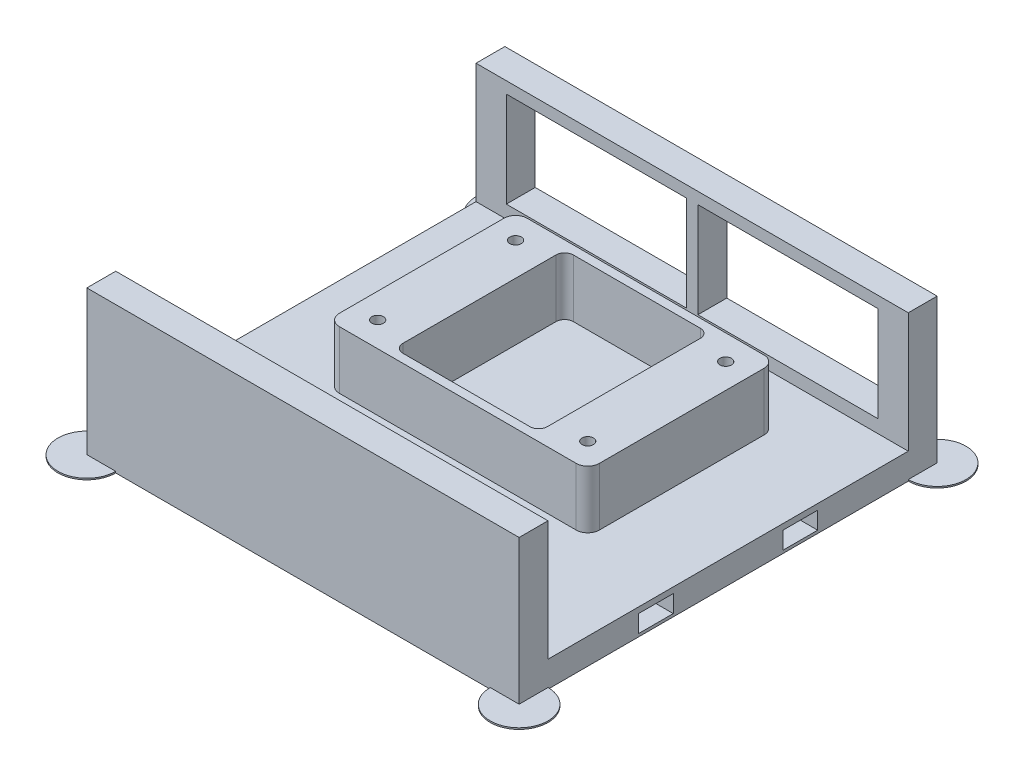
SolidWorks part; units mm, degrees
material "ABS"
ref_plane "Front Plane" through (0, 0, 0) normal (0, 0, 1) x (1, 0, 0)
ref_plane "Top Plane" through (0, 0, 0) normal (0, 1, 0) x (1, 0, 0)
ref_plane "Right Plane" through (0, 0, 0) normal (1, 0, 0) x (0, 0, -1)
sketch "Sketch1" plane through (0, 0, 0) normal (0, 1, 0) x (1, 0, 0)
  line L0 (-150, 0) -> (150, 0) construction
  line L1 (-150, 45) -> (-150, -45)
  line L2 (140.0883, -41.1583) -> (79.948, -63.0476) construction
  line L3 (-140.0883, 41.1583) -> (-142.4825, 47.7362) construction
  line L4 (-140.0883, 41.1583) -> (-79.948, 63.0476) construction
  line L5 (-150, 45) -> (-74.8246, 72.3616)
  line L6 (-79.948, 63.0476) -> (-82.3421, 69.6255) construction
  line L7 (-143, 32) -> (-143, -32) construction
  line L8 (-140.0883, -41.1583) -> (-142.4825, -47.7362) construction
  line L9 (-79.948, -63.0476) -> (-82.3421, -69.6255) construction
  line L10 (-140.0883, -41.1583) -> (-79.948, -63.0476) construction
  line L11 (-150, -45) -> (-74.8246, -72.3616)
  line L12 (0, 74.8501) -> (0, -82.9126) construction
  line L13 (79.948, -63.0476) -> (82.3421, -69.6255) construction
  line L14 (140.0883, -41.1583) -> (142.4825, -47.7362) construction
  line L15 (143, 32) -> (143, -32) construction
  line L16 (79.948, 63.0476) -> (82.3421, 69.6255) construction
  line L17 (140.0883, 41.1583) -> (79.948, 63.0476) construction
  line L18 (140.0883, 41.1583) -> (142.4825, 47.7362) construction
  line L19 (150, -45) -> (74.8246, -72.3616)
  line L20 (150, 45) -> (74.8246, 72.3616)
  line L21 (150, 45) -> (150, -45)
  line L22 (-74.8246, 72.3616) -> (74.8246, 72.3616)
  line L23 (-74.8246, -72.3616) -> (74.8246, -72.3616)
  point P0 (0, 0)
  point P3 (-150, 0)
  point P10 (-143, 0)
  point P13 (0, 0)
  point P37 (143, 0)
  dimension "D1" = 7
  dimension "D2" = 90
  dimension "D3" = 64
  dimension "D4" = 300
  dimension "D5" = 7
  dimension "D6" = 8
  dimension "D7" = 80
  dimension "D8" = 110
extrude "Boss-Extrude1" add sketch "Sketch1" along normal blind 8
sketch "Sketch2" plane through (0, 8, 0) normal (0, 1, 0) x (1, 0, 0)
  line L0 (0, 72.3616) -> (0, -72.3616) construction
  line L1 (74.8246, 72.3616) -> (-74.8246, 72.3616) construction
  line L2 (-74.8246, -72.3616) -> (74.8246, -72.3616) construction
  line L3 (-74.8246, -72.3616) -> (-74.8246, -62.3616) construction
  line L4 (-74.8246, -62.3616) -> (-64.3246, -62.3616) construction
  line L5 (-64.3246, -62.3616) -> (-64.3246, -72.3616) construction
  line L6 (-64.3246, -72.3616) -> (-74.8246, -72.3616) construction
  line L7 (64.3246, -72.3616) -> (74.8246, -72.3616) construction
  line L8 (64.3246, -62.3616) -> (64.3246, -72.3616) construction
  line L9 (74.8246, -62.3616) -> (64.3246, -62.3616) construction
  line L10 (74.8246, -72.3616) -> (74.8246, -62.3616) construction
  line L11 (-150, 0) -> (150, 0) construction
  line L12 (-150, 45) -> (-150, -45) construction
  line L13 (150, -45) -> (150, 45) construction
  line L14 (74.8246, 72.3616) -> (74.8246, 62.3616)
  line L15 (74.8246, 62.3616) -> (64.3246, 62.3616)
  line L16 (64.3246, 62.3616) -> (64.3246, 72.3616)
  line L17 (64.3246, 72.3616) -> (74.8246, 72.3616)
  line L18 (-64.3246, 72.3616) -> (-74.8246, 72.3616)
  line L19 (-64.3246, 62.3616) -> (-64.3246, 72.3616)
  line L20 (-74.8246, 62.3616) -> (-64.3246, 62.3616)
  line L21 (-74.8246, 72.3616) -> (-74.8246, 62.3616)
  dimension "D1" = 10.5
  dimension "D2" = 10
extrude "Boss-Extrude2" add sketch "Sketch2" along normal blind 37.5
sketch "Sketch4" plane through (0, 8, 0) normal (0, 1, 0) x (1, 0, 0)
  line L1 (-64.3246, 72.3616) -> (64.3246, 72.3616)
  line L2 (-64.3246, 72.3616) -> (-64.3246, 62.3616)
  line L3 (-64.3246, 62.3616) -> (64.3246, 62.3616)
  line L4 (64.3246, 72.3616) -> (64.3246, 62.3616)
extrude "Boss-Extrude4" add sketch "Sketch4" along normal blind 4.5
sketch "Sketch5" plane through (0, 8, 0) normal (0, 1, 0) x (1, 0, 0)
  line L0 (-74.8246, 62.3616) -> (-87.0406, 57.9153)
  line L1 (-74.8246, 72.3616) -> (-150, 45) construction
  line L2 (-74.8246, 72.3616) -> (-74.8246, 62.3616)
  line L3 (-74.8246, 72.3616) -> (-150, 45)
  line L4 (-87.0406, 57.9153) -> (-140.6031, 38.4202)
  line L5 (-150, 45) -> (-140.6031, 38.4202) construction
  line L6 (-74.8246, -72.3616) -> (-74.8246, -62.3616)
  line L7 (-140.6031, 38.4202) -> (-143.4222, 37.3941)
  line L8 (-150, 45) -> (-143.4222, 37.3941) construction
  line L9 (-150, 0) -> (-74.8246, 0) construction
  line L10 (-150, 45) -> (-150, -45) construction
  line L11 (-79.6003, 0) -> (86.9407, 0) construction
  line L12 (-124.0599, 0) -> (-121.8599, 0) construction
  line L13 (-74.8246, -62.3616) -> (-87.0406, -57.9153)
  line L14 (-140.6031, -38.4202) -> (-143.4222, -37.3941)
  line L15 (-87.0406, -57.9153) -> (-140.6031, -38.4202)
  line L16 (-150, -45) -> (-143.4222, -37.3941) construction
  line L17 (-74.8246, -72.3616) -> (-150, -45)
  line L18 (-143.4222, 37.3941) -> (-143.4222, -37.3941)
  line L19 (-150, 45) -> (-150, -45)
  line L20 (0, 72.1209) -> (0, -72.3616) construction
  line L21 (-74.8246, -72.3616) -> (74.8246, -72.3616) construction
  line L22 (150, -45) -> (143.4222, -37.3941) construction
  line L23 (150, 0) -> (74.8246, 0) construction
  line L24 (150, 45) -> (143.4222, 37.3941) construction
  line L25 (150, 45) -> (140.6031, 38.4202) construction
  line L26 (150, 45) -> (150, -45)
  line L27 (143.4222, 37.3941) -> (143.4222, -37.3941)
  line L28 (74.8246, -72.3616) -> (150, -45)
  line L29 (87.0406, -57.9153) -> (140.6031, -38.4202)
  line L30 (140.6031, -38.4202) -> (143.4222, -37.3941)
  line L31 (74.8246, -62.3616) -> (87.0406, -57.9153)
  line L32 (140.6031, 38.4202) -> (143.4222, 37.3941)
  line L33 (74.8246, -72.3616) -> (74.8246, -62.3616)
  line L34 (87.0406, 57.9153) -> (140.6031, 38.4202)
  line L35 (74.8246, 72.3616) -> (150, 45)
  line L36 (74.8246, 72.3616) -> (74.8246, 62.3616)
  line L37 (74.8246, 62.3616) -> (87.0406, 57.9153)
  dimension "D1" = 13
  dimension "D2" = 55
  dimension "D3" = 3
extrude "Boss-Extrude5" add sketch "Sketch5" along normal blind 10
sketch "Sketch6" plane through (0, 45.5, 0) normal (0, 1, 0) x (1, 0, 0)
  line L1 (74.8246, 72.3616) -> (-74.8246, 72.3616)
  line L2 (74.8246, 72.3616) -> (74.8246, 62.3616)
  line L3 (74.8246, 62.3616) -> (-74.8246, 62.3616)
  line L4 (-74.8246, 72.3616) -> (-74.8246, 62.3616)
extrude "Boss-Extrude6" add sketch "Sketch6" along normal blind 4
sketch "Sketch7" plane through (32.0094, 0, -87.9451) normal (0.342, 0, -0.9397) x (-0.9397, 0, -0.342)
  line L0 (-85.563, 18) -> (-85.563, 0) construction
  line L1 (-125.563, 18) -> (-45.563, 18) construction
  line L2 (-125.563, 0) -> (-45.563, 0) construction
  line L3 (-113.853, 13) -> (-85.563, 13) construction
  circle A0 centre (-113.853, 13) radius 2.5
  circle A1 centre (-57.273, 13) radius 2.5
  dimension "D1" = 56.58
  dimension "D2" = 5
  dimension "D3" = 5
extrude "Cut-Extrude1" cut sketch "Sketch7" against normal up to next
ref_plane "Plane1" through (0, 0, 0) normal (1, 0, 0) x (0, 0, -1)
mirror "Mirror1" about plane through (0, 0, 0) normal (1, 0, 0) of "Cut-Extrude1"
ref_plane "Plane2" through (0, 0, 0) normal (0, 0, -1) x (-1, 0, 0)
mirror "Mirror2" about plane through (0, 0, 0) normal (0, 0, -1) of "Cut-Extrude1", "Mirror1"
sketch "Sketch8" plane through (150, 0, 0) normal (1, 0, 0) x (0, 0, -1)
  line L0 (0, 18) -> (0, 0) construction
  line L1 (-45, 18) -> (45, 18) construction
  line L2 (-28.29, 13) -> (28.29, 13) construction
  line L3 (0, -27.775) -> (0, 27.775) construction
  circle A0 centre (-28.29, 13) radius 2.5
  circle A1 centre (28.29, 13) radius 2.5
  point P8 (0, 13)
  dimension "D1" = 56.58
  dimension "D3" = 5
  dimension "D2" = 5
extrude "Cut-Extrude2" cut sketch "Sketch8" against normal up to next
mirror "Mirror3" about plane through (0, 0, 0) normal (1, 0, 0) of "Cut-Extrude2"
sketch "Sketch9" plane through (0, 18, 0) normal (0, 1, 0) x (1, 0, 0)
  line L0 (143.4222, 23) -> (150, 23)
  line L1 (143.4222, 37.3941) -> (143.4222, -37.3941) construction
  line L2 (150, -45) -> (150, 45) construction
  line L3 (150, 23) -> (150, 45)
  line L4 (150, 45) -> (134.0252, 50.8143)
  line L5 (150, 45) -> (74.8246, 72.3616) construction
  line L6 (134.0252, 50.8143) -> (130.8113, 41.9841)
  line L7 (74.8246, 62.3616) -> (143.4222, 37.3941) construction
  line L8 (130.8113, 41.9841) -> (143.4222, 37.3941)
  line L9 (143.4222, 37.3941) -> (143.4222, 23)
  line L12 (74.8246, 72.3616) -> (90.7994, 66.5473)
  line L13 (90.7994, 66.5473) -> (87.5854, 57.717)
  line L14 (87.5854, 57.717) -> (74.8246, 62.3616)
  line L15 (74.8246, 72.3616) -> (74.8246, 62.3616) construction
  line L16 (74.8246, 62.3616) -> (74.8246, 72.3616)
  line L17 (0, -70.7131) -> (0, 92.4677) construction
  line L18 (-74.8246, 62.3616) -> (-74.8246, 72.3616)
  line L19 (-87.5854, 57.717) -> (-74.8246, 62.3616)
  line L20 (-90.7994, 66.5473) -> (-87.5854, 57.717)
  line L21 (-74.8246, 72.3616) -> (-90.7994, 66.5473)
  line L22 (-143.4222, 37.3941) -> (-143.4222, 23)
  line L23 (-130.8113, 41.9841) -> (-143.4222, 37.3941)
  line L24 (-134.0252, 50.8143) -> (-130.8113, 41.9841)
  line L25 (-150, 45) -> (-134.0252, 50.8143)
  line L26 (-150, 23) -> (-150, 45)
  line L27 (-143.4222, 23) -> (-150, 23)
  line L28 (150, 0) -> (-150, 0) construction
  line L29 (-150, 45) -> (-150, -45) construction
  line L30 (143.4222, -37.3941) -> (143.4222, -23)
  line L31 (130.8113, -41.9841) -> (143.4222, -37.3941)
  line L32 (134.0252, -50.8143) -> (130.8113, -41.9841)
  line L33 (150, -45) -> (134.0252, -50.8143)
  line L34 (150, -23) -> (150, -45)
  line L35 (143.4222, -23) -> (150, -23)
  line L36 (-143.4222, -23) -> (-150, -23)
  line L37 (-150, -23) -> (-150, -45)
  line L38 (-150, -45) -> (-134.0252, -50.8143)
  line L39 (-134.0252, -50.8143) -> (-130.8113, -41.9841)
  line L40 (-130.8113, -41.9841) -> (-143.4222, -37.3941)
  line L41 (-143.4222, -37.3941) -> (-143.4222, -23)
  line L42 (-74.8246, -72.3616) -> (-90.7994, -66.5473)
  line L43 (-90.7994, -66.5473) -> (-87.5854, -57.717)
  line L44 (-87.5854, -57.717) -> (-74.8246, -62.3616)
  line L45 (-74.8246, -62.3616) -> (-74.8246, -72.3616)
  line L46 (74.8246, -62.3616) -> (74.8246, -72.3616)
  line L47 (87.5854, -57.717) -> (74.8246, -62.3616)
  line L48 (90.7994, -66.5473) -> (87.5854, -57.717)
  line L49 (74.8246, -72.3616) -> (90.7994, -66.5473)
  dimension "D1" = 22
  dimension "D2" = 17
  dimension "D3" = 17
extrude "Boss-Extrude8" add sketch "Sketch9" along normal blind 63
sketch "Sketch10" plane through (32.0094, 0, -87.9451) normal (0.342, 0, -0.9397) x (-0.9397, 0, -0.342)
  line L0 (-85.563, 0) -> (-85.563, 86.9159) construction
  line L1 (-125.563, 0) -> (-45.563, 0) construction
  line L2 (-113.853, 13) -> (-113.853, 74) construction
  circle A0 centre (-113.853, 74) radius 2.5
  circle A1 centre (-113.853, 13) radius 2.5 construction
  circle A2 centre (-57.273, 74) radius 2.5
  dimension "D1" = 61
extrude "Cut-Extrude3" cut sketch "Sketch10" against normal up to next
mirror "Mirror4" about plane through (0, 0, 0) normal (1, 0, 0) of "Cut-Extrude3"
mirror "Mirror5" about plane through (0, 0, 0) normal (0, 0, -1) of "Cut-Extrude3", "Mirror4"
sketch "Sketch11" plane through (150, 0, 0) normal (1, 0, 0) x (0, 0, -1)
  line L0 (-28.29, 13) -> (-28.29, 74) construction
  line L1 (0, 18) -> (0, 79.1024) construction
  line L2 (-23, 18) -> (23, 18) construction
  circle A0 centre (-28.29, 74) radius 2.5
  circle A1 centre (-28.29, 13) radius 2.5 construction
  circle A2 centre (28.29, 74) radius 2.5
  dimension "D1" = 61
extrude "Cut-Extrude4" cut sketch "Sketch11" against normal up to next
mirror "Mirror6" about plane through (0, 0, 0) normal (1, 0, 0) of "Cut-Extrude4"
sketch "Sketch12" plane through (0, 81, 0) normal (0, 1, 0) x (1, 0, 0)
  line L0 (130.8113, 41.9841) -> (87.5854, 57.717)
  line L1 (87.5854, 57.717) -> (90.7994, 66.5473)
  line L2 (90.7994, 66.5473) -> (134.0252, 50.8143)
  line L3 (134.0252, 50.8143) -> (130.8113, 41.9841)
  line L4 (0, 103.9036) -> (0, -116.4859) construction
  line L5 (143.4222, 23) -> (150, 23)
  line L6 (143.4222, 23) -> (143.4222, -23)
  line L7 (143.4222, -23) -> (150, -23)
  line L8 (150, 23) -> (150, -23)
  line L9 (150, 0) -> (-150, 0) construction
  line L10 (-150, 23) -> (-150, -23) construction
  line L11 (134.0252, -50.8143) -> (130.8113, -41.9841)
  line L12 (90.7994, -66.5473) -> (134.0252, -50.8143)
  line L13 (87.5854, -57.717) -> (90.7994, -66.5473)
  line L14 (130.8113, -41.9841) -> (87.5854, -57.717)
  line L15 (-130.8113, -41.9841) -> (-87.5854, -57.717)
  line L16 (-87.5854, -57.717) -> (-90.7994, -66.5473)
  line L17 (-90.7994, -66.5473) -> (-134.0252, -50.8143)
  line L18 (-134.0252, -50.8143) -> (-130.8113, -41.9841)
  line L19 (-150, 23) -> (-150, -23)
  line L20 (-143.4222, -23) -> (-150, -23)
  line L21 (-143.4222, 23) -> (-143.4222, -23)
  line L22 (-143.4222, 23) -> (-150, 23)
  line L23 (-134.0252, 50.8143) -> (-130.8113, 41.9841)
  line L24 (-90.7994, 66.5473) -> (-134.0252, 50.8143)
  line L25 (-87.5854, 57.717) -> (-90.7994, 66.5473)
  line L26 (-130.8113, 41.9841) -> (-87.5854, 57.717)
extrude "Boss-Extrude9" add sketch "Sketch12" against normal blind 12
sketch "Sketch13" plane through (0, 8, 0) normal (0, 1, 0) x (1, 0, 0)
  line L0 (0, 62.3616) -> (0, -72.3616) construction
  line L1 (-41, 46.2316) -> (-29, 46.2316)
  line L2 (-45, 42.2316) -> (-45, -14.7684)
  line L3 (-41, -18.7684) -> (-29, -18.7684)
  line L4 (45, 42.2316) -> (45, -14.7684)
  line L5 (-74.8246, 62.3616) -> (74.8246, 62.3616) construction
  line L6 (-74.8246, -72.3616) -> (74.8246, -72.3616) construction
  line L7 (-25, 40.2316) -> (-25, -12.7684)
  line L8 (25, 40.2316) -> (25, -12.7684)
  line L9 (29, 46.2316) -> (41, 46.2316)
  line L10 (29, -18.7684) -> (41, -18.7684)
  line L11 (-25, 46.2316) -> (25, 46.2316) construction
  line L12 (-25, -18.7684) -> (25, -18.7684) construction
  line L13 (-29, 46.2316) -> (29, 46.2316)
  line L14 (-22, 43.2316) -> (22, 43.2316)
  line L15 (-22, -15.7684) -> (22, -15.7684)
  line L16 (-29, -18.7684) -> (29, -18.7684)
  arc A0 (-45, -14.7684) -> (-41, -18.7684) centre (-41, -14.7684) ccw
  arc A1 (41, -18.7684) -> (45, -14.7684) centre (41, -14.7684) ccw
  arc A2 (41, 46.2316) -> (45, 42.2316) centre (41, 42.2316) cw
  arc A3 (-41, 46.2316) -> (-45, 42.2316) centre (-41, 42.2316) ccw
  arc A4 (-25, -12.7684) -> (-22, -15.7684) centre (-22, -12.7684) ccw
  arc A5 (25, -12.7684) -> (22, -15.7684) centre (22, -12.7684) cw
  arc A6 (25, 40.2316) -> (22, 43.2316) centre (22, 40.2316) ccw
  arc A7 (-25, 40.2316) -> (-22, 43.2316) centre (-22, 40.2316) cw
  point P10 (0, 46.2316)
  point P15 (45, -18.7684)
  point P18 (45, 46.2316)
  point P21 (-45, 46.2316)
  dimension "D4" = 4
  dimension "D7" = 3
  dimension "D9" = 3
  dimension "D1" = 65
  dimension "D2" = 90
  dimension "D3" = 16.13
  dimension "D5" = 20
  dimension "D6" = 25
  dimension "D8" = 3
extrude "Boss-Extrude10" add sketch "Sketch13" along normal blind 20
sketch "Sketch14" plane through (0, 28, 0) normal (0, 1, 0) x (1, 0, 0)
  line L0 (-45, 42.2316) -> (-45, -14.7684) construction
  line L1 (-36.37, 37.6066) -> (-36.37, -10.1434) construction
  line L2 (-45, 13.7316) -> (-25, 13.7316) construction
  line L3 (-25, -12.7684) -> (-25, 40.2316) construction
  circle A0 centre (-36.37, 37.6066) radius 2
  circle A1 centre (-36.37, -10.1434) radius 2
  point P10 (-36.37, 13.7316)
  dimension "D1" = 4
  dimension "D2" = 47.75
  dimension "D3" = 8.63
extrude "Cut-Extrude5" cut sketch "Sketch14" against normal blind 10
mirror "Mirror7" about plane through (0, 0, 0) normal (1, 0, 0) of "Cut-Extrude5"
sketch "Sketch15" plane through (0, 8, 0) normal (0, 1, 0) x (1, 0, 0)
  line L1 (-74.8246, -72.3616) -> (74.8246, -72.3616)
  line L2 (-74.8246, -72.3616) -> (-74.8246, -62.3616)
  line L3 (-74.8246, -62.3616) -> (74.8246, -62.3616)
  line L4 (74.8246, -72.3616) -> (74.8246, -62.3616)
extrude "Boss-Extrude11" add sketch "Sketch15" along normal blind 41.5
sketch "Sketch16" plane through (0, 0, -72.3616) normal (0, 0, -1) x (-1, 0, 0)
  line L0 (-74.8246, 81) -> (-47.5, 81)
  line L1 (0, 0) -> (0, 104.0722) construction
  line L2 (0, 45.1) -> (0, -45.1) construction
  line L3 (74.8246, 81) -> (47.5, 81)
  line L4 (-74.8246, 49.5) -> (74.8246, 49.5) construction
  line L5 (-74.8246, 81) -> (-74.8246, 49.5)
  line L6 (-74.8246, 49.5) -> (74.8246, 49.5)
  line L7 (74.8246, 49.5) -> (74.8246, 81)
  arc A0 (-47.5, 81) -> (47.5, 81) centre (0, 101.0635) ccw
  dimension "D1" = 95
sketch "Sketch17" plane through (0, 81, 0) normal (0, 1, 0) x (1, 0, 0)
  line L0 (150, -45) -> (123.1193, -26.178) construction
  line L1 (150, 0) -> (-150, 0) construction
  line L2 (150, -45) -> (150, 45) construction
  line L3 (-150, 45) -> (-150, -45) construction
  line L4 (0, 76.5626) -> (0, -108.8084) construction
  circle A0 centre (145.0851, -41.5585) radius 2
  circle A1 centre (145.0851, 41.5585) radius 2
  circle A2 centre (-145.0851, 41.5585) radius 2
  circle A3 centre (-145.0851, -41.5585) radius 2
  dimension "D2" = 4
  dimension "D1" = 55
  dimension "D3" = 6
extrude "Cut-Extrude6" cut sketch "Sketch17" against normal blind 10
sketch "Esquisse1" plane through (0, 8, 0) normal (0, 1, 0) x (1, 0, 0)
  line L0 (-132, 21) -> (-132, -21)
  line L1 (-132, -21) -> (-120, -21)
  line L2 (-120, -21) -> (-120, 21)
  line L3 (-120, 21) -> (-132, 21)
  line L4 (0, 62.3616) -> (0, -62.3616) construction
  line L5 (-74.8246, 62.3616) -> (74.8246, 62.3616) construction
  line L6 (74.8246, -62.3616) -> (-74.8246, -62.3616) construction
  line L7 (120, 21) -> (132, 21)
  line L8 (120, -21) -> (120, 21)
  line L9 (132, -21) -> (120, -21)
  line L10 (132, 21) -> (132, -21)
  line L11 (-150, 0) -> (150, 0) construction
  line L12 (-150, 45) -> (-150, -45) construction
  line L13 (150, -45) -> (150, 45) construction
  line L14 (-74.8246, 62.3616) -> (-74.8246, -62.3616) construction
  line L15 (-95.8246, 31) -> (-53.8246, 31)
  line L16 (-95.8246, 31) -> (-95.8246, 19)
  line L17 (-95.8246, 19) -> (-53.8246, 19)
  line L18 (-53.8246, 31) -> (-53.8246, 19)
  line L19 (-95.8246, 31) -> (-53.8246, 19) construction
  line L20 (-95.8246, 19) -> (-53.8246, 31) construction
  line L21 (-95.8246, -19) -> (-53.8246, -31) construction
  line L22 (-95.8246, -31) -> (-53.8246, -19) construction
  line L23 (-53.8246, -31) -> (-53.8246, -19)
  line L24 (-95.8246, -19) -> (-53.8246, -19)
  line L25 (-95.8246, -31) -> (-95.8246, -19)
  line L26 (-95.8246, -31) -> (-53.8246, -31)
  line L27 (95.8246, -31) -> (53.8246, -19) construction
  line L28 (95.8246, -19) -> (53.8246, -31) construction
  line L29 (95.8246, 19) -> (53.8246, 31) construction
  line L30 (95.8246, 31) -> (53.8246, 19) construction
  line L31 (95.8246, -31) -> (53.8246, -31)
  line L32 (95.8246, -31) -> (95.8246, -19)
  line L33 (95.8246, -19) -> (53.8246, -19)
  line L34 (53.8246, -31) -> (53.8246, -19)
  line L35 (53.8246, 31) -> (53.8246, 19)
  line L36 (95.8246, 19) -> (53.8246, 19)
  line L37 (95.8246, 31) -> (95.8246, 19)
  line L38 (95.8246, 31) -> (53.8246, 31)
  point P20 (-120, 0)
  point P21 (-74.8246, 25)
  point P34 (-74.8246, -25)
  point P43 (74.8246, -25)
  point P44 (74.8246, 25)
  dimension "D1" = 12
  dimension "D2" = 42
  dimension "D3" = 120
  dimension "D4" = 25
extrude "Enlèv. mat.-Extru.1" cut sketch "Esquisse1" against normal blind 6 from offset 2 offset against normal yes
sketch "Esquisse2" plane through (0, 0, 0) normal (0, -1, 0) x (1, 0, 0)
  line L8 (-150, -45) -> (-74.8246, -72.3616)
  line L9 (-74.8246, -72.3616) -> (74.8246, -72.3616)
  line L10 (74.8246, -72.3616) -> (150, -45)
  line L11 (150, -45) -> (150, 45)
  line L12 (150, 45) -> (74.8246, 72.3616)
  line L13 (74.8246, 72.3616) -> (-74.8246, 72.3616)
  line L14 (-74.8246, 72.3616) -> (-150, 45)
  line L15 (-150, 45) -> (-150, -45)
  line L16 (-150, -45) -> (-74.8246, -72.3616)
  line L17 (-74.8246, -72.3616) -> (74.8246, -72.3616)
  line L18 (74.8246, -72.3616) -> (150, -45)
  line L19 (150, -45) -> (150, 45)
  line L20 (150, 45) -> (74.8246, 72.3616)
  line L21 (74.8246, 72.3616) -> (-74.8246, 72.3616)
  line L22 (-74.8246, 72.3616) -> (-150, 45)
  line L23 (-150, 45) -> (-150, -45)
  dimension "D1" = 0
extrude "Boss.-Extru.1" add sketch "Esquisse2" along normal blind 1
fillet "Congé1" radius 5 4 edges at (150, 40, 45) (150, 40, -45) (-150, 40, -45) (-150, 40, 45)
sketch "Esquisse3" plane through (-32.0094, 0, 87.9451) normal (-0.342, 0, 0.9397) x (0.9397, 0, 0.342)
  line L0 (-62.563, 69) -> (-62.563, 18) construction
  line L1 (-108.563, 69) -> (-56.563, 69)
  line L2 (-108.563, 69) -> (-108.563, 14)
  line L3 (-108.563, 14) -> (-56.563, 14)
  line L4 (-56.563, 69) -> (-56.563, 14)
  line L5 (-108.563, 18) -> (-62.563, 18) construction
  circle A0 centre (-57.273, 13) radius 2.5
  circle A2 centre (-57.273, 13) radius 2.5 construction
  line M5 (-62.563, 69) -> (-62.563, 18)
  line M6 (-62.563, 18) -> (-108.563, 18)
  circle M9 centre (-57.273, 13) radius 2.5
  dimension "D1" = 6
  dimension "D2" = 4
extrude "Enlèv. mat.-Extru.2" cut sketch "Esquisse3" against normal blind 10 contours L4 L1 L2 L3 M5 M6 M9
sketch "Esquisse5" plane through (-150, 0, 0) normal (-1, 0, 0) x (0, 0, 1)
  line L0 (23, 69) -> (23, 18) construction
  line L1 (-23, 69) -> (29, 69)
  line L2 (-23, 69) -> (-23, 14)
  line L3 (-23, 14) -> (29, 14)
  line L4 (29, 69) -> (29, 14)
  line L7 (-23, 18) -> (23, 18) construction
  dimension "D1" = 6
  dimension "D2" = 4
extrude "Enlèv. mat.-Extru.3" cut sketch "Esquisse5" against normal blind 10
sketch "Esquisse6" plane through (-32.0094, 0, -87.9451) normal (-0.342, 0, -0.9397) x (-0.9397, 0, 0.342)
  line L0 (108.563, 69) -> (108.563, 18) construction
  line L1 (62.563, 69) -> (114.563, 69)
  line L2 (62.563, 69) -> (62.563, 14)
  line L3 (62.563, 14) -> (114.563, 14)
  line L4 (114.563, 69) -> (114.563, 14)
  line L5 (62.563, 18) -> (108.563, 18) construction
  dimension "D1" = 6
  dimension "D2" = 4
extrude "Enlèv. mat.-Extru.4" cut sketch "Esquisse6" against normal blind 10
sketch "Esquisse7" plane through (32.0094, 0, -87.9451) normal (0.342, 0, -0.9397) x (-0.9397, 0, -0.342)
  line L0 (-62.563, 69) -> (-62.563, 18) construction
  line L1 (-108.563, 69) -> (-56.563, 69)
  line L2 (-108.563, 69) -> (-108.563, 14)
  line L3 (-108.563, 14) -> (-56.563, 14)
  line L4 (-56.563, 69) -> (-56.563, 14)
  line L5 (-108.563, 18) -> (-62.563, 18) construction
  dimension "D1" = 6
  dimension "D2" = 4
extrude "Enlèv. mat.-Extru.5" cut sketch "Esquisse7" against normal blind 10
sketch "Esquisse8" plane through (150, 0, 0) normal (1, 0, 0) x (0, 0, -1)
  line L0 (23, 69) -> (23, 18) construction
  line L1 (-23, 69) -> (29, 69)
  line L2 (-23, 69) -> (-23, 14)
  line L3 (-23, 14) -> (29, 14)
  line L4 (29, 69) -> (29, 14)
  line L5 (-23, 18) -> (23, 18) construction
  dimension "D1" = 6
  dimension "D2" = 4
extrude "Enlèv. mat.-Extru.6" cut sketch "Esquisse8" against normal blind 10
sketch "Esquisse9" plane through (32.0094, 0, 87.9451) normal (0.342, 0, 0.9397) x (0.9397, 0, -0.342)
  line L0 (108.563, 69) -> (108.563, 18) construction
  line L1 (62.563, 69) -> (114.563, 69)
  line L2 (62.563, 69) -> (62.563, 14)
  line L3 (62.563, 14) -> (114.563, 14)
  line L4 (114.563, 69) -> (114.563, 14)
  line L5 (62.563, 18) -> (108.563, 18) construction
  dimension "D1" = 6
  dimension "D2" = 4
extrude "Enlèv. mat.-Extru.7" cut sketch "Esquisse9" against normal blind 10
sketch "Esquisse10" plane through (-150, 0, 0) normal (-1, 0, 0) x (0, 0, 1)
  line L1 (-255.7005, -191.9117) -> (109.0426, -191.9117)
  line L2 (-255.7005, -191.9117) -> (-255.7005, 136.0454)
  line L3 (-255.7005, 136.0454) -> (109.0426, 136.0454)
  line L4 (109.0426, -191.9117) -> (109.0426, 136.0454)
  line L5 (-255.7005, -191.9117) -> (109.0426, 136.0454) construction
  line L6 (-255.7005, 136.0454) -> (109.0426, -191.9117) construction
  point P0 (-73.3289, -27.9332)
sketch "Esquisse11" plane through (0, 12.5, 0) normal (0, 1, 0) x (1, 0, 0)
  line L0 (0, 62.3616) -> (0, 72.3616) construction
  line L1 (-64.3246, 62.3616) -> (64.3246, 62.3616) construction
  line L2 (64.3246, 72.3616) -> (-64.3246, 72.3616) construction
  line L4 (2, 62.3616) -> (-2, 62.3616)
  line L5 (2, 62.3616) -> (2, 72.3616)
  line L6 (2, 72.3616) -> (-2, 72.3616)
  line L7 (-2, 62.3616) -> (-2, 72.3616)
  point P10 (0, 62.3616)
  dimension "D1" = 4
extrude "Boss.-Extru.2" add sketch "Esquisse11" along normal up to next
sketch "Esquisse12" plane through (0, 81, 0) normal (0, 1, 0) x (1, 0, 0)
  line L0 (74.8246, -74.9512) -> (74.8246, 102.2345)
  line L1 (74.8246, 102.2345) -> (-74.8246, 102.2345)
  line L2 (-74.8246, 102.2345) -> (-74.8246, -146.9264)
  line L3 (-74.8246, -146.9264) -> (-203.1994, -126.0576)
  line L4 (-203.1994, -126.0576) -> (-188.0221, 94.6459)
  line L5 (-188.0221, 94.6459) -> (-19.2917, 194.6851)
  line L6 (-19.2917, 194.6851) -> (183.8222, 119.309)
  line L7 (183.8222, 119.309) -> (217.581, -44.1202)
  line L8 (217.581, -44.1202) -> (162.3923, -136.492)
  line L9 (162.3923, -136.492) -> (87.8202, -136.492)
  line L10 (87.8202, -136.492) -> (74.8246, -74.9512)
  line L11 (74.8246, -72.3616) -> (74.8246, -62.3616) construction
  line L12 (-74.8246, -72.3616) -> (-74.8246, -62.3616) construction
extrude "Enlèv. mat.-Extru.8" cut sketch "Esquisse12" against normal through all
sketch "Esquisse13" plane through (0, -1, 0) normal (0, -1, 0) x (1, 0, 0)
  line L0 (0, -72.3616) -> (0, 72.3616) construction
  line L1 (-74.8246, -72.3616) -> (74.8246, -72.3616) construction
  line L2 (74.8246, 72.3616) -> (-74.8246, 72.3616) construction
  line L3 (74.8246, 0) -> (-74.8246, 0) construction
  line L4 (74.8246, -72.3616) -> (74.8246, 72.3616) construction
  line L5 (-74.8246, 72.3616) -> (-74.8246, -72.3616) construction
  circle A0 centre (74.8246, -72.3616) radius 10
  circle A1 centre (-74.8246, -72.3616) radius 10
  circle A2 centre (-74.8246, 72.3616) radius 10
  circle A3 centre (74.8246, 72.3616) radius 10
  dimension "D1" = 20
extrude "Boss.-Extru.3" add sketch "Esquisse13" against normal blind 0.5
